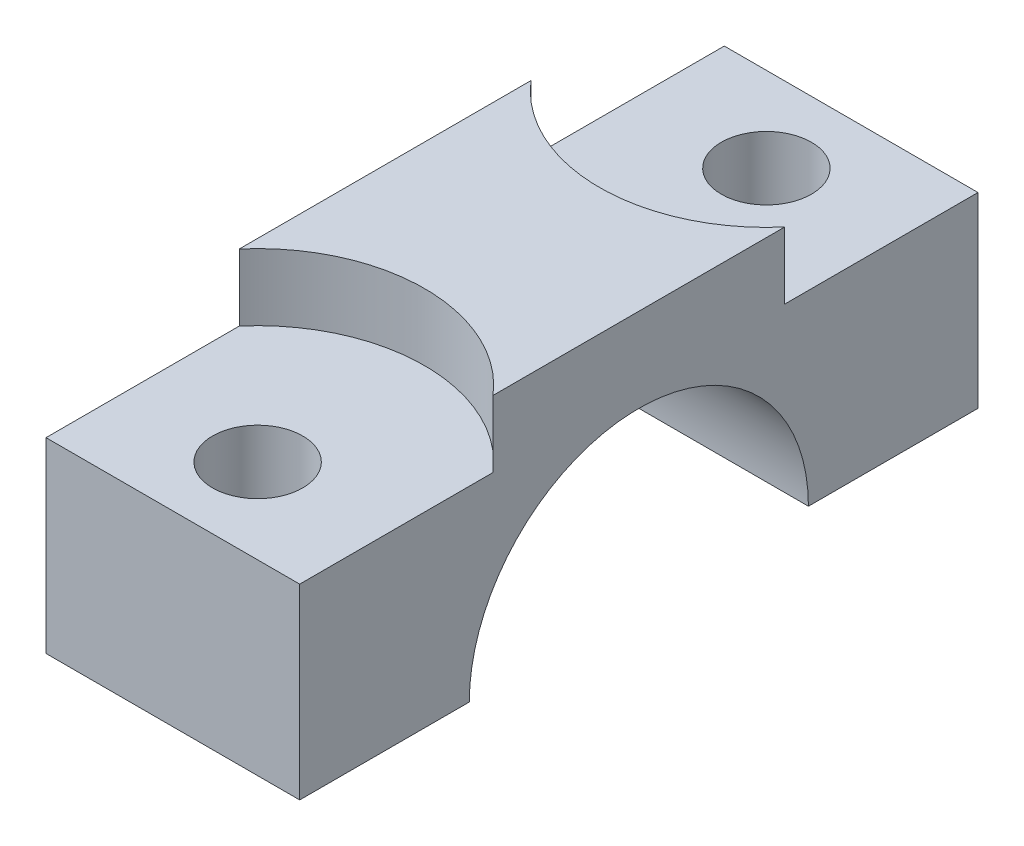
SolidWorks part; units mm, degrees
ref_plane "Front Plane" through (0, 0, 0) normal (0, 0, 1) x (1, 0, 0)
ref_plane "Top Plane" through (0, 0, 0) normal (0, 1, 0) x (1, 0, 0)
ref_plane "Right Plane" through (0, 0, 0) normal (1, 0, 0) x (0, 0, -1)
sketch "Sketch1" plane through (0, 0, 0) normal (1, 0, 0) x (0, 0, -1)
  line L1 (-25.4, 19) -> (25.4, 19)
  line L2 (-25.4, 19) -> (-25.4, 0)
  line L3 (-25.4, 0) -> (25.4, 0)
  line L4 (25.4, 19) -> (25.4, 0)
  circle A0 centre (0, 0) radius 12.7
  dimension "D1" = 25.4
  dimension "D2" = 50.8
  dimension "D3" = 19
extrude "Boss-Extrude1" add sketch "Sketch1" along normal mid plane 19 contours A0 L3 L4 L1 L2
sketch "Sketch2" plane through (0, 19, 0) normal (0, -1, 0) x (1, 0, 0)
  line L0 (0, 25.4) -> (0, 12.7) construction
  line L1 (9.5, 25.4) -> (-9.5, 25.4) construction
  line L2 (9.5, 12.7) -> (-9.5, 12.7) construction
  line L3 (0, -12.7) -> (0, -25.4) construction
  line L4 (9.5, -12.7) -> (-9.5, -12.7) construction
  line L5 (9.5, -25.4) -> (-9.5, -25.4) construction
  point P12 (0, 19.05)
  point P13 (0, -19.05)
hole_wizard "CBORE for M12 Hex Head Cap Screw2" positions "3DSketch5" profile "Sketch7" counterbore size "M12" standard "ISO" end condition through all
sketch3d "3DSketch5"
  point P0 (0, 19, -19.05)
  point P3 (0, 19, 19.05)
sketch "Sketch7" plane through (0, 19, -19.05) normal (1, 0, 0) x (0, 0, 1)
  line L0 (0, 0) -> (0, 19)
  line L1 (0, 19) -> (3.375, 19)
  line L3 (3.375, 19) -> (3.375, 5)
  line L4 (3.375, 5) -> (12.5, 5)
  line L5 (12.5, 5) -> (12.5, 0)
  line L7 (12.5, 0) -> (0, 0)
  line L11 (0, -6.35) -> (0, 107.95) construction
  dimension "Thru Hole Dia." = 6.75
  dimension "Thru Hole Depth" = 19
  dimension "C'Bore Dia." = 25
  dimension "C'Bore Depth" = 5
